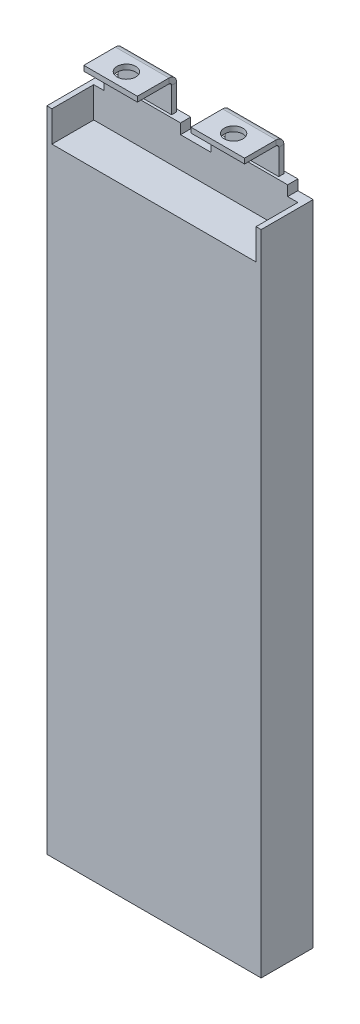
SolidWorks part; units mm, degrees
ref_plane "Front Plane" through (0, 0, 0) normal (0, 0, 1) x (1, 0, 0)
ref_plane "Top Plane" through (0, 0, 0) normal (0, 1, 0) x (1, 0, 0)
ref_plane "Right Plane" through (0, 0, 0) normal (1, 0, 0) x (0, 0, -1)
sketch "Sketch1" plane through (0, 0, 0) normal (0, 0, 1) x (1, 0, 0)
  line L1 (-21, 0) -> (21, 0)
  line L2 (-21, 0) -> (-21, 127)
  line L3 (-21, 127) -> (21, 127)
  line L4 (21, 0) -> (21, 127)
  dimension "D1" = 127
  dimension "D2" = 42
extrude "Boss-Extrude1" add sketch "Sketch1" along normal mid plane 10.2
ref_plane "Tab Mid Plane" through (0, 0, -4.1) normal (0, 0, -1) x (-1, 0, 0)
sketch "Sketch2" plane through (0, 0, 5.1) normal (0, 0, 1) x (1, 0, 0)
  line L0 (21, 127) -> (-21, 127) construction
  line L1 (-20, 127) -> (20, 127)
  line L2 (-20, 127) -> (-20, 121)
  line L3 (-20, 121) -> (20, 121)
  line L4 (20, 127) -> (20, 121)
  line L5 (-21, 127) -> (-21, 0) construction
  point P8 (0, 127)
  dimension "D1" = 1
  dimension "D2" = 6
extrude "Cut-Extrude1" cut sketch "Sketch2" against normal offset from surface (8.2 mm away) 1 up to plane "Tab Mid Plane"
sketch "Sketch3" plane through (0, 0, -4.1) normal (0, 0, -1) x (-1, 0, 0)
  line L0 (-21, 127) -> (21, 127) construction
  line L1 (-18, 127) -> (-3, 127)
  line L2 (-18, 127) -> (-18, 129)
  line L3 (-18, 129) -> (-3, 129)
  line L4 (-3, 127) -> (-3, 129)
  line L5 (-3, 127) -> (3, 127) construction
  line L6 (3, 127) -> (18, 127)
  line L7 (3, 127) -> (3, 129)
  line L8 (3, 129) -> (18, 129)
  line L9 (18, 127) -> (18, 129)
  point P10 (-10.5, 129)
  point P11 (10.5, 129)
  point P12 (0, 127)
  point P13 (5.25, 129)
  dimension "D1" = 21
  dimension "D2" = 2
  dimension "D3" = 15
extrude "Boss-Extrude2" add sketch "Sketch3" along normal mid plane 2
sketch "Tab Profile" plane through (0, 129, 0) normal (0, 1, 0) x (1, 0, 0)
  line L0 (-18, 5.1) -> (-3, 3.1) construction
  line L1 (-15.75, 4.6) -> (-5.25, 4.6)
  line L2 (-15.75, 4.6) -> (-15.75, 3.6)
  line L3 (-15.75, 3.6) -> (-5.25, 3.6)
  line L4 (-5.25, 4.6) -> (-5.25, 3.6)
  line L5 (5.25, 4.6) -> (15.75, 4.6)
  line L6 (5.25, 4.6) -> (5.25, 3.6)
  line L7 (5.25, 3.6) -> (15.75, 3.6)
  line L8 (15.75, 4.6) -> (15.75, 3.6)
  line L9 (3, 5.1) -> (18, 3.1) construction
  line L10 (-15.75, 3.6) -> (-5.25, 4.6) construction
  line L11 (5.25, 3.6) -> (15.75, 4.6) construction
  point P16 (-10.5, 4.1)
  point P17 (10.5, 4.1)
  dimension "D1" = 10.5
  dimension "D2" = 1
sketch "Tab Bend" plane through (0, 0, 0) normal (1, 0, 0) x (0, 0, -1)
  line L0 (4.1, 129) -> (4.1, 134)
  line L1 (5.1, 129) -> (3.1, 129) construction
  line L2 (3.1, 135) -> (-3.1, 135)
  arc A0 (4.1, 134) -> (3.1, 135) centre (3.1, 134) ccw
  point P6 (0, 135)
  dimension "D2" = 1
  dimension "D1" = 5
sweep "Tabs" add profiles "Tab Profile" path "Tab Bend"
hole_wizard "#6 Clearance Hole1" positions "Sketch9" profile "Sketch10" hole size "#6" standard "ANSI Inch"
sketch "Sketch9" plane through (0, 135.5, 0) normal (0, 1, 0) x (1, 0, 0)
  line L0 (-15.75, 3.1) -> (-5.25, -3.1) construction
  point P0 (-10.5, 0)
sketch "Sketch10" plane through (-10.5, 135.5, 0) normal (1, 0, 0) x (0, 0, 1)
  line L0 (0, 0) -> (0, 1)
  line L1 (0, 1) -> (1.8288, 1)
  line L2 (1.8288, 1) -> (1.8288, 0)
  line L5 (1.8288, 0) -> (0, 0)
  line L11 (0, -6.35) -> (0, 107.95) construction
  dimension "Thru Hole Dia." = 3.6576
  dimension "Thru Hole Depth" = 1
hole_wizard "#6 Clearance Hole2" positions "Sketch11" profile "Sketch12" hole size "#6" standard "ANSI Inch"
sketch "Sketch11" plane through (0, 135.5, 0) normal (0, 1, 0) x (1, 0, 0)
  line L0 (5.25, 3.1) -> (15.75, -3.1) construction
  point P0 (10.5, 0)
  point P8 (0, 0)
sketch "Sketch12" plane through (10.5, 135.5, 0) normal (1, 0, 0) x (0, 0, 1)
  line L0 (0, 0) -> (0, 1)
  line L1 (0, 1) -> (1.8288, 1)
  line L2 (1.8288, 1) -> (1.8288, 0)
  line L5 (1.8288, 0) -> (0, 0)
  line L11 (0, -6.35) -> (0, 107.95) construction
  dimension "Thru Hole Dia." = 3.6576
  dimension "Thru Hole Depth" = 1
